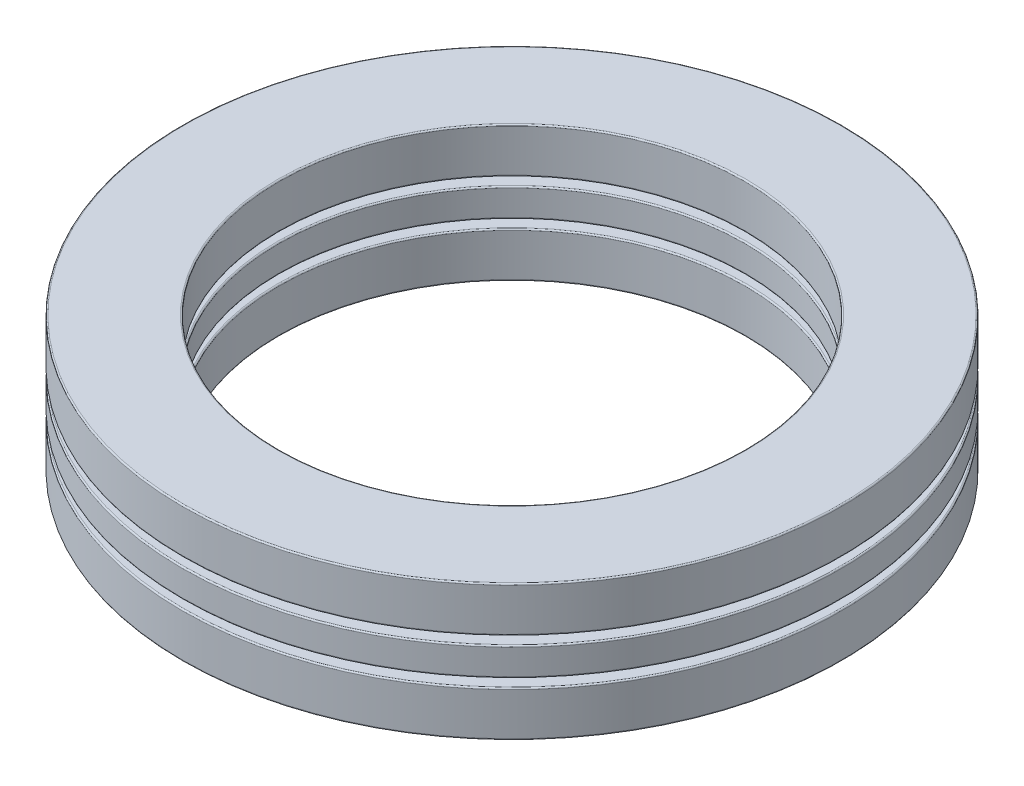
SolidWorks part; units mm, degrees
ref_plane "Front Plane" through (0, 0, 0) normal (0, 0, 1) x (1, 0, 0)
ref_plane "Top Plane" through (0, 0, 0) normal (0, 1, 0) x (1, 0, 0)
ref_plane "Right Plane" through (0, 0, 0) normal (1, 0, 0) x (0, 0, -1)
sketch "Sketch1" plane through (0, 0, 0) normal (1, 0, 0) x (0, 0, -1)
  line L0 (-26.9875, 0) -> (26.9875, 0) construction
  line L1 (0, -5.5499) -> (0, 5.5499) construction
  line L2 (-26.9875, 1.1562) -> (-19.0881, 1.1562)
  line L3 (-26.9875, 1.1562) -> (-26.9875, -1.1562)
  line L4 (-26.9875, -1.1562) -> (-19.0881, -1.1562)
  line L5 (-19.0881, 1.1562) -> (-19.0881, -1.1562)
  line L6 (-23.0378, 1.85) -> (-23.0378, -1.85) construction
  circle A0 centre (-23.0378, 0) radius 1.85 construction
  point P13 (-23.0378, 1.1562)
  dimension "D1" = 3.6999
  dimension "OD" = 53.975
  dimension "Shaft Dia" = 38.1762
  dimension "Th" = 11.0998
  dimension "D2" = 2.3125
revolve "Revolve1" add sketch "Sketch1" angle 360 about L1
sketch "Sketch3" plane through (0, 0, 0) normal (1, 0, 0) x (0, 0, -1)
  line L0 (-23.0378, 1.85) -> (-23.0378, -1.85)
  arc A0 (-23.0378, 1.85) -> (-23.0378, -1.85) centre (-23.0378, 0) ccw
  circle A1 centre (-23.0378, 0) radius 1.85 construction
revolve "Cut-Revolve1" cut sketch "Sketch3" angle 360 about L0
sketch "Sketch2" plane through (0, 0, 0) normal (1, 0, 0) x (0, 0, -1)
  line L0 (-23.0378, 1.85) -> (-23.0378, -1.85)
  arc A0 (-23.0378, 1.85) -> (-23.0378, -1.85) centre (-23.0378, 0) ccw
  circle A2 centre (-23.0378, 0) radius 1.85 construction
revolve "Revolve2" add sketch "Sketch2" angle 360 about L0
ref_axis "Axis1" through (0, 5.5499, 0) along (0, -1, 0)
pattern_circular "CirPattern1" count 11 every 32.727 about axis through (0, 5.5499, 0) along (0, -1, 0) of bodies 187
pattern_circular "CirPattern2" count 11 every 32.727 about axis through (0, 0, 0) along (0, 1, 0) of "Cut-Revolve1"
sketch "Sketch4" plane through (0, 0, 0) normal (1, 0, 0) x (0, 0, -1)
  line L0 (-26.9875, 1.1562) -> (-26.9875, -1.1562) construction
  line L1 (-26.9875, 1.85) -> (-19.0881, 1.85)
  line L2 (-26.9875, 1.85) -> (-26.9875, 5.5499)
  line L3 (-26.9875, 5.5499) -> (-19.0881, 5.5499)
  line L4 (-19.0881, 1.85) -> (-19.0881, 5.5499)
  line L5 (-26.9875, -5.5499) -> (-19.0881, -5.5499)
  line L6 (-26.9875, -5.5499) -> (-26.9875, -1.85)
  line L7 (-26.9875, -1.85) -> (-19.0881, -1.85)
  line L8 (-19.0881, -5.5499) -> (-19.0881, -1.85)
  line L9 (-23.0378, 1.85) -> (-23.0378, -1.85) construction
  line L10 (-19.0881, 1.1562) -> (-19.0881, -1.1562) construction
  line L11 (0, 0) -> (-26.9875, 0) construction
  line L12 (-26.9875, 0) -> (26.9875, 0) construction
  dimension "Ht" = 11.0998
revolve "Revolve3" add sketch "Sketch4" angle 360 about L1
fillet "Fillet1" radius 0.111 4 edges at (0, 1.85, -19.0881) (0, 5.5499, -19.0881) (0, 1.85, -26.9875) (0, 5.5499, -26.9875)
fillet "Fillet2" radius 0.111 4 edges at (0, -1.1562, -19.0881) (0, 1.1562, -19.0881) (0, -1.1562, -26.9875) (0, 1.1562, -26.9875)
fillet "Fillet3" radius 0.111 4 edges at (0, -5.5499, -19.0881) (0, -1.85, -19.0881) (0, -5.5499, -26.9875) (0, -1.85, -26.9875)
equation "\"D1@Sketch1\" = \"Th@Sketch1\"/3"
equation "\"D2@Sketch1\" = \"D1@Sketch1\"*.625"
equation "\"Balls@CirPattern1\" = \"OD@Sketch1\"*5"
equation "\"Angle@CirPattern1\" = 360/\"Balls@CirPattern1\""
equation "\"D1@CirPattern2\" = \"Balls@CirPattern1\""
equation "\"D2@CirPattern2\" = \"Angle@CirPattern1\""
equation "\"D1@Fillet1\" = \"Th@Sketch1\"*.01"
equation "\"D1@Fillet2\" = \"D1@Fillet1\""
equation "\"D1@Fillet3\" = \"D1@Fillet1\""
